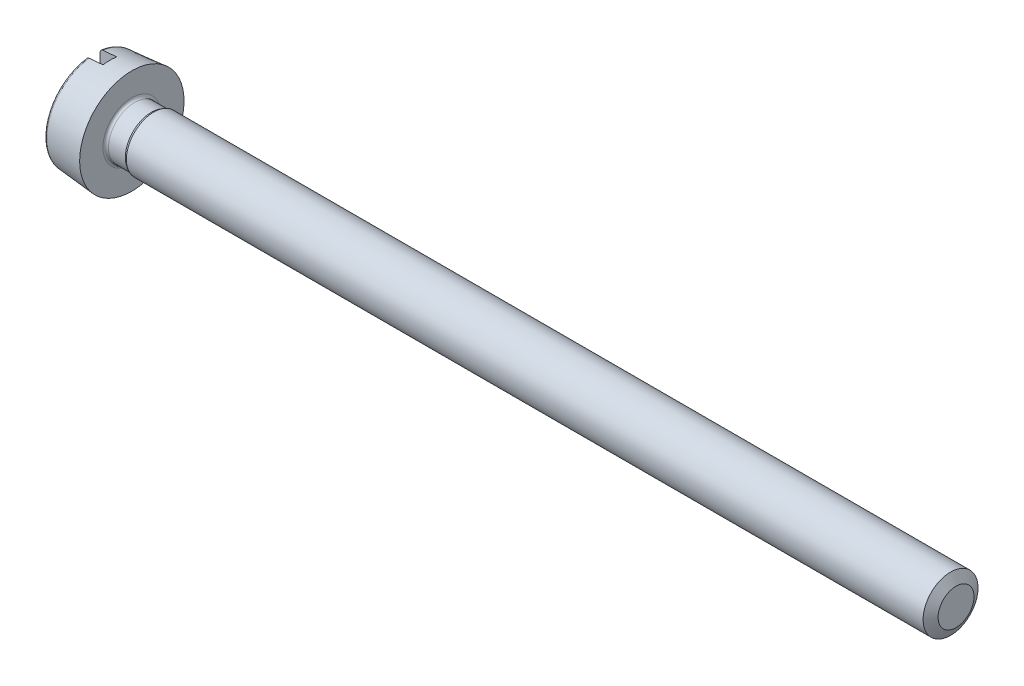
SolidWorks part; units mm, degrees
revolve "基体-旋转" add sketch "草图1" angle 360 about L0
sketch "草图1" plane through (0, 0, 0) normal (0, 0, 1) x (1, 0, 0)
  line L0 (0, 0) -> (31.4, 0) construction
  line L1 (0, 0) -> (0, 1.6859)
  line L2 (1.4, 1.9) -> (0.0913, 1.7855)
  line L3 (1.4, 1.9) -> (1.4, 1.05)
  line L4 (1.5, 0.95) -> (2.1134, 0.95)
  line L5 (2.1134, 0.95) -> (2.2, 1)
  line L6 (2.2, 1) -> (31.4, 1)
  line L7 (31.4, 1) -> (31.4, 0)
  line L8 (0, 0) -> (31.4, 0)
  arc A0 (1.5, 0.95) -> (1.4, 1.05) centre (1.5, 1.05) cw
  arc A1 (0, 1.6859) -> (0.0913, 1.7855) centre (0.1, 1.6859) cw
  dimension "r" = 0.1
  dimension "D10" = 0.1
  dimension "D1" = 1.9
  dimension "d" = 2
  dimension "a" = 0.8
  dimension "D8" = 30
  dimension "D2" = 85
  dimension "k" = 1.4
  dimension "dk" = 3.8
  dimension "l" = 30
cosmetic thread "装饰螺纹线1" parameters "D1"=3.3866, "D2"=1.2
ref_plane "前视" through (0, 0, 0) normal (0, 0, 1) x (1, 0, 0)
ref_plane "上视" through (0, 0, 0) normal (0, 1, 0) x (1, 0, 0)
ref_plane "右视" through (0, 0, 0) normal (1, 0, 0) x (0, 0, -1)
sketch "尺寸草图" plane through (0, 0, 0) normal (0, 0, 1) x (1, 0, 0)
  line L0 (0, 0) -> (21.4, 0)
  point P3 (0.6, 0)
  point P4 (0.8, 0)
  point P5 (2, 0)
  point P6 (3.8, 0)
  point P7 (0.5, 0)
  point P8 (3.1989, 0)
  point P9 (3.656, 0)
  point P10 (4.0948, 0)
  point P11 (21, 0)
  point P12 (21.3, 0)
  point P13 (1.4, 0)
  dimension "r" = 0.1
  dimension "d" = 2
  dimension "a" = 0.8
  dimension "k" = 1.4
  dimension "dk" = 3.8
  dimension "t" = 0.6
  dimension "l" = 20
  dimension "n" = 0.5
  dimension "p" = 0.4
sketch "草图2" plane through (0, 0, 0) normal (-1, 0, 0) x (0, 0, 1)
  line L0 (0, 0) -> (0, -1.8809) construction
  line L3 (0.25, 1.8835) -> (0.25, -1.8835)
  line L5 (-0.25, 1.8835) -> (-0.25, -1.8835)
  circle A1 centre (0, 0) radius 1.9 construction
  arc A2 (0.25, 1.8835) -> (-0.25, 1.8835) centre (0, 0) ccw
  arc A3 (-0.25, -1.8835) -> (0.25, -1.8835) centre (0, 0) ccw
  dimension "n" = 0.5
extrude "切除-拉伸1" cut sketch "草图2" against normal blind 0.6
sketch "草图3" plane through (0, 0, 0) normal (0, 1, 0) x (1, 0, 0)
  line L0 (31.2, 1) -> (31.6, 1)
  line L2 (31.6, 1) -> (31.4, 0.6536)
  line L3 (31.4, 0.6536) -> (31.2, 1)
  line L4 (31.4, -1.6037) -> (31.4, 3.368) construction
  line L10 (31.4, -1) -> (31.4, 1) construction
  line L11 (0, 0) -> (7.2232, 0) construction
  dimension "D1" = 120
  dimension "D2" = 0.3464
  dimension "D3" = 1
revolve "切除-旋转1" cut sketch "草图3" angle 360 about L11
pattern_linear "阵列(线性)1" [suppressed] count 74 along (1, 0, 0)
equation "\"a@草图1\" = \"a@尺寸草图\" "
equation "\"r@草图1\" = \"r@尺寸草图\" "
equation "\"d@草图1\" = \"d@尺寸草图\" "
equation "\"k@草图1\" = \"k@尺寸草图\" "
equation "\"dk@草图1\" = \"dk@尺寸草图\" "
equation "\"n@草图2\" = \"n@尺寸草图\" "
equation "\"t@切除-拉伸1\" = \"t@尺寸草图\" "
equation "\"p@阵列(线性)1\" = \"p@尺寸草图\" "
equation "\"D2@草图3\" = \"p@尺寸草图\" * 0.866"
equation "\"D3@草图3\" = \"d@草图1\" / 2"
equation "\"D1@草图1\" = \"d@草图1\" - \"r@草图1\""
equation "\"D1@阵列(线性)1\" =  ( \"l@草图1\" - \"a@草图1\" )  / \"p@阵列(线性)1\" + 1"
